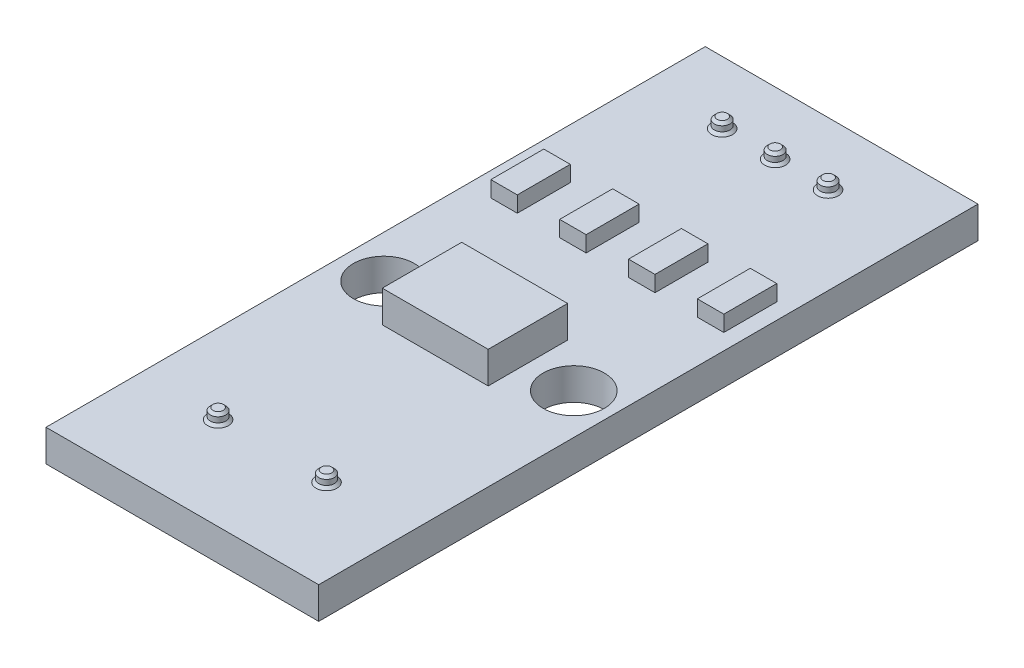
SolidWorks part; units mm, degrees
ref_plane "Front Plane" through (0, 0, 0) normal (0, 0, 1) x (1, 0, 0)
ref_plane "Top Plane" through (0, 0, 0) normal (0, 1, 0) x (1, 0, 0)
ref_plane "Right Plane" through (0, 0, 0) normal (1, 0, 0) x (0, 0, -1)
sketch "Sketch2" plane through (0, 0, 0) normal (0, 1, 0) x (1, 0, 0)
  line L1 (0, 0) -> (13.081, 0)
  line L2 (0, 0) -> (0, 31.623)
  line L3 (0, 31.623) -> (13.081, 31.623)
  line L4 (13.081, 0) -> (13.081, 31.623)
  line L5 (6.5405, 31.623) -> (6.5405, 0) construction
  line L6 (0, 15.8115) -> (13.081, 15.8115) construction
  point P48 (6.5405, 15.8115)
  dimension "D1" = 31.623
  dimension "D2" = 13.081
extrude "Boss-Extrude1" add sketch "Sketch2" along normal blind 1.524
sketch "Sketch3" plane through (0, 1.524, 0) normal (0, 1, 0) x (1, 0, 0)
  line L0 (3.81, 28.623) -> (6.35, 28.623)
  line L1 (0, 31.623) -> (3.81, 31.623)
  line L2 (0, 31.623) -> (0, 28.623)
  line L3 (0, 28.623) -> (3.81, 28.623)
  line L4 (3.81, 31.623) -> (3.81, 28.623)
  line L5 (1.905, 28.623) -> (1.905, 31.623) construction
  line L6 (0, 30.123) -> (3.81, 30.123) construction
  line L7 (6.35, 28.623) -> (8.89, 28.623)
  line L8 (3.81, 4.445) -> (9.01, 4.445)
  line L9 (0, 31.623) -> (3.81, 31.623)
  line L10 (0, 31.623) -> (0, 4.445)
  line L11 (0, 4.445) -> (3.81, 4.445)
  line L12 (3.81, 31.623) -> (3.81, 4.445)
  line L13 (1.905, 4.445) -> (1.905, 31.623) construction
  line L14 (0, 18.034) -> (3.81, 18.034) construction
  circle A0 centre (3.81, 28.623) radius 0.375
  circle A1 centre (6.35, 28.623) radius 0.375
  circle A2 centre (8.89, 28.623) radius 0.375
  circle A3 centre (3.81, 4.445) radius 0.375
  circle A4 centre (9.01, 4.445) radius 0.375
  point P152 (1.905, 30.123)
  point P355 (1.905, 18.034)
  dimension "D3" = 0.75
  dimension "D6" = 0.75
  dimension "D7" = 0.75
  dimension "D11" = 0.75
  dimension "D12" = 0.75
  dimension "D1" = 3
  dimension "D2" = 3.81
  dimension "D4" = 2.54
  dimension "D5" = 2.54
  dimension "D8" = 27.178
  dimension "D9" = 3.81
  dimension "D10" = 5.2
extrude "Boss-Extrude3" add sketch "Sketch3" against normal blind 4.064 and the other way blind 0.508 contours A0 | A1 | A2 | A3 | A4
chamfer "Chamfer2" distance 0.127 angle 45 18 edges at (9.01, 1.524, -4.82) (9.01, 2.032, -4.07) (3.81, 1.524, -4.82) (3.81, 2.032, -4.07) (9.01, -2.54, -4.07) (3.81, -2.54, -4.07) (3.81, 0, -28.998) (3.81, -2.54, -28.248) (8.89, -2.54, -28.248) (8.89, 0, -28.998) (6.35, -2.54, -28.248) (6.35, 0, -28.998) (3.81, 1.524, -28.998) (6.35, 1.524, -28.998) (8.89, 1.524, -28.998) (8.89, 2.032, -28.248) (6.35, 2.032, -28.248) (3.81, 2.032, -28.248)
sketch "Sketch4" plane through (0, 1.524, 0) normal (0, 1, 0) x (1, 0, 0)
  line L0 (2.413, 22.733) -> (4.445, 22.733)
  line L1 (0, 31.623) -> (1.143, 31.623)
  line L2 (0, 31.623) -> (0, 22.733)
  line L3 (0, 22.733) -> (1.143, 22.733)
  line L4 (1.143, 31.623) -> (1.143, 22.733)
  line L5 (0.5715, 22.733) -> (0.5715, 31.623) construction
  line L6 (0, 27.178) -> (1.143, 27.178) construction
  line L7 (1.143, 22.733) -> (2.413, 22.733)
  line L8 (1.143, 22.733) -> (1.143, 20.193)
  line L9 (1.143, 20.193) -> (2.413, 20.193)
  line L10 (2.413, 22.733) -> (2.413, 20.193)
  line L11 (1.778, 20.193) -> (1.778, 22.733) construction
  line L12 (1.143, 21.463) -> (2.413, 21.463) construction
  line L13 (5.715, 22.733) -> (7.747, 22.733)
  line L14 (4.445, 22.733) -> (5.715, 22.733)
  line L15 (4.445, 22.733) -> (4.445, 20.193)
  line L16 (4.445, 20.193) -> (5.715, 20.193)
  line L17 (5.715, 22.733) -> (5.715, 20.193)
  line L18 (5.08, 20.193) -> (5.08, 22.733) construction
  line L19 (4.445, 21.463) -> (5.715, 21.463) construction
  line L20 (9.017, 22.733) -> (11.049, 22.733)
  line L21 (7.747, 22.733) -> (9.017, 22.733)
  line L22 (7.747, 22.733) -> (7.747, 20.193)
  line L23 (7.747, 20.193) -> (9.017, 20.193)
  line L24 (9.017, 22.733) -> (9.017, 20.193)
  line L25 (8.382, 20.193) -> (8.382, 22.733) construction
  line L26 (7.747, 21.463) -> (9.017, 21.463) construction
  line L28 (11.049, 22.733) -> (12.319, 22.733)
  line L29 (11.049, 22.733) -> (11.049, 20.193)
  line L30 (11.049, 20.193) -> (12.319, 20.193)
  line L31 (12.319, 22.733) -> (12.319, 20.193)
  line L32 (11.684, 20.193) -> (11.684, 22.733) construction
  line L33 (11.049, 21.463) -> (12.319, 21.463) construction
  point P67 (5.08, 21.463)
  point P72 (8.382, 21.463)
  point P92 (0.5715, 27.178)
  point P117 (11.684, 21.463)
  point P177 (1.778, 21.463)
  dimension "D1" = 8.89
  dimension "D2" = 1.143
  dimension "D3" = 2.54
  dimension "D4" = 1.27
  dimension "D5" = 2.032
  dimension "D6" = 2.54
  dimension "D7" = 1.27
  dimension "D8" = 2.032
  dimension "D9" = 2.54
  dimension "D10" = 1.27
  dimension "D11" = 2.032
  dimension "D12" = 2.54
  dimension "D13" = 1.27
extrude "Boss-Extrude4" add sketch "Sketch4" along normal blind 0.762 contours L10 L7 L8 L9 | L17 L14 L15 L16 | L24 L21 L22 L23 | L31 L28 L29 L30
sketch "Sketch5" plane through (0, 1.524, 0) normal (0, 1, 0) x (1, 0, 0)
  line L1 (0, 31.623) -> (3.81, 31.623)
  line L2 (0, 31.623) -> (0, 16.129)
  line L3 (0, 16.129) -> (3.81, 16.129)
  line L4 (3.81, 31.623) -> (3.81, 16.129)
  line L5 (1.905, 16.129) -> (1.905, 31.623) construction
  line L6 (0, 23.876) -> (3.81, 23.876) construction
  line L7 (3.81, 16.129) -> (8.89, 16.129)
  line L8 (3.81, 16.129) -> (3.81, 12.319)
  line L9 (3.81, 12.319) -> (8.89, 12.319)
  line L10 (8.89, 16.129) -> (8.89, 12.319)
  line L11 (6.35, 12.319) -> (6.35, 16.129) construction
  line L12 (3.81, 14.224) -> (8.89, 14.224) construction
  point P73 (6.35, 14.224)
  point P108 (1.905, 23.876)
  dimension "D1" = 15.494
  dimension "D2" = 3.81
  dimension "D3" = 3.81
  dimension "D4" = 5.08
extrude "Boss-Extrude5" add sketch "Sketch5" along normal blind 1.524 contours L10 L7 L8 L9
sketch "Sketch6" plane through (0, 1.524, 0) normal (0, 1, 0) x (1, 0, 0)
  circle A0 centre (2.0305, 14.1749) radius 1.4628
  circle A1 centre (11.1385, 14.1749) radius 1.4702
extrude "Cut-Extrude1" cut sketch "Sketch6" against normal blind 1.524
